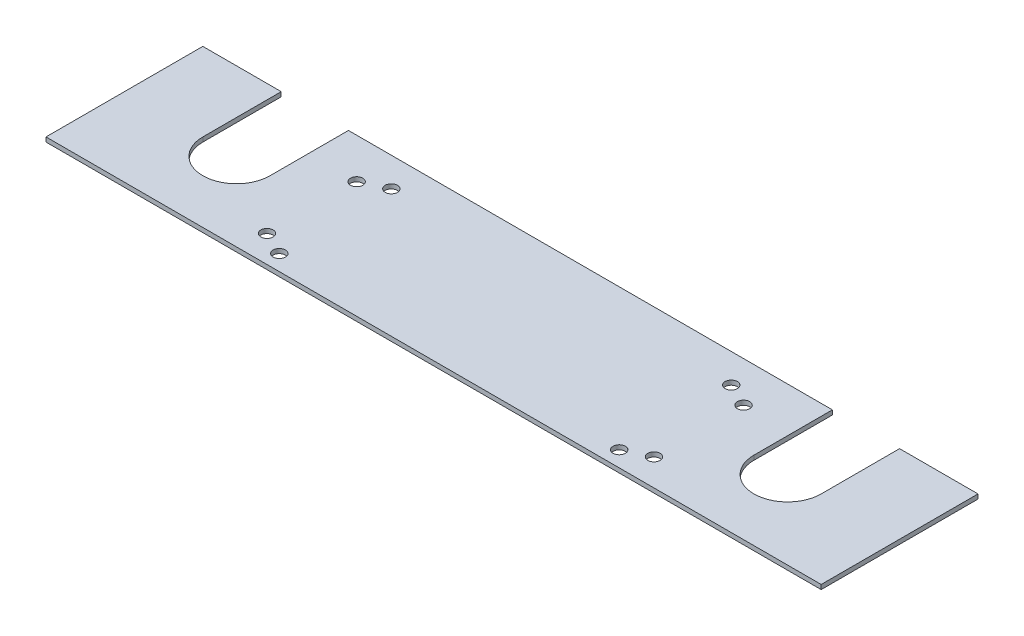
SolidWorks part; units mm, degrees
ref_plane "Front Plane" through (0, 0, 0) normal (0, 0, 1) x (1, 0, 0)
ref_plane "Top Plane" through (0, 0, 0) normal (0, 1, 0) x (1, 0, 0)
ref_plane "Right Plane" through (0, 0, 0) normal (1, 0, 0) x (0, 0, -1)
sketch "Sketch1" plane through (0, 0, 0) normal (0, 0, 1) x (1, 0, 0)
  line L1 (173, -1) -> (-173, -1)
  line L2 (173, -1) -> (173, 1)
  line L3 (173, 1) -> (-173, 1)
  line L4 (-173, -1) -> (-173, 1)
  line L5 (173, -1) -> (-173, 1) construction
  line L6 (173, 1) -> (-173, -1) construction
  point P0 (0, 0)
  dimension "D1" = 346
  dimension "D2" = 2
extrude "Boss-Extrude1" add sketch "Sketch1" along normal blind 70
sketch "Sketch2" plane through (0, 1, 0) normal (0, 1, 0) x (1, 0, 0)
  line L0 (173, -13) -> (75.86, -13) construction
  line L1 (173, -70) -> (173, 0) construction
  line L2 (173, -63) -> (75.86, -63) construction
  line L3 (173, 0) -> (-173, 0) construction
  line L4 (173, -70) -> (-173, -70) construction
  point P10 (86.36, -18)
  point P11 (86.36, -58)
  dimension "D1" = 97.14
  dimension "D2" = 13
  dimension "D3" = 7
  dimension "D4" = 5
  dimension "D5" = 10.5
  dimension "D6" = 5
  dimension "D7" = 10.5
hole_wizard "M5 Clearance Hole1" positions "3DSketch1" profile "Sketch3" hole size "M5" standard "ISO" end condition through all
sketch3d "3DSketch1"
  point P0 (86.36, 1, 18)
  point P3 (75.86, 1, 13)
  point P6 (86.36, 1, 58)
  point P9 (75.86, 1, 63)
sketch "Sketch3" plane through (86.36, 1, 18) normal (1, 0, 0) x (0, 0, 1)
  line L0 (0, 0) -> (0, 2)
  line L1 (0, 2) -> (2.75, 2)
  line L2 (2.75, 2) -> (2.75, 0)
  line L5 (2.75, 0) -> (0, 0)
  line L11 (0, -6.35) -> (0, 107.95) construction
  dimension "Thru Hole Dia." = 5.5
  dimension "Thru Hole Depth" = 2
mirror "Mirror1" about plane through (0, 0, 0) normal (1, 0, 0) of "M5 Clearance Hole1"
sketch "Sketch4" plane through (0, 1, 0) normal (0, 1, 0) x (1, 0, 0)
  line L0 (173, -35) -> (123, -35) construction
  line L1 (173, -70) -> (173, 0) construction
  line L2 (0, 0) -> (0, -70) construction
  line L3 (173, -70) -> (-173, -70) construction
  line L4 (138, -35) -> (138, 0)
  line L5 (173, 0) -> (-173, 0) construction
  line L6 (108, -35) -> (108, 0)
  line L7 (108, 0) -> (138, 0)
  line L8 (-108, -35) -> (-108, 0)
  line L9 (-108, 0) -> (-138, 0)
  line L10 (-138, -35) -> (-138, 0)
  arc A0 (108, -35) -> (138, -35) centre (123, -35) ccw
  arc A1 (-108, -35) -> (-138, -35) centre (-123, -35) cw
  dimension "D2" = 30
  dimension "D1" = 50
extrude "Cut-Extrude1" cut sketch "Sketch4" against normal blind 10
